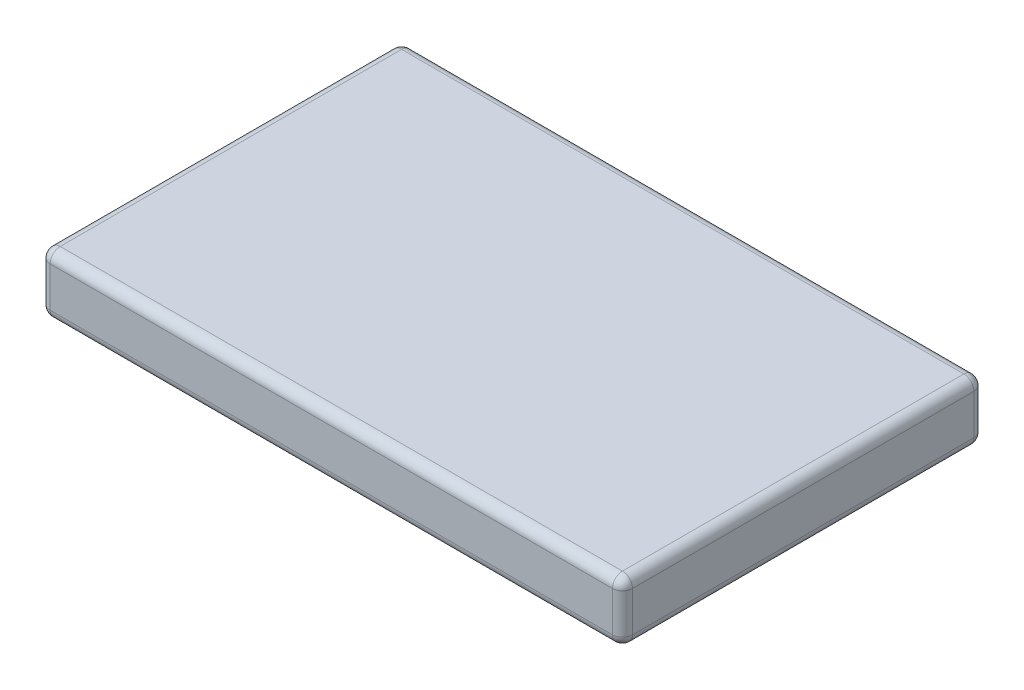
SolidWorks part; units mm, degrees
ref_plane "Plano frontal" through (0, 0, 0) normal (0, 0, 1) x (1, 0, 0)
ref_plane "Plano superior" through (0, 0, 0) normal (0, 1, 0) x (1, 0, 0)
ref_plane "Plano direito" through (0, 0, 0) normal (1, 0, 0) x (0, 0, -1)
sketch "Esboço1" plane through (0, 0, 0) normal (0, 1, 0) x (1, 0, 0)
  line L1 (29, 18) -> (-29, 18)
  line L2 (29, 18) -> (29, -18)
  line L3 (29, -18) -> (-29, -18)
  line L4 (-29, 18) -> (-29, -18)
  line L5 (29, 18) -> (-29, -18) construction
  line L6 (29, -18) -> (-29, 18) construction
  point P0 (0, 0)
  dimension "D1" = 36
  dimension "D2" = 58
extrude "Ressalto-extrusão1" add sketch "Esboço1" along normal blind 6
fillet "Filete1" radius 1 12 edges at (0, 0, 18) (29, 0, 0) (0, 0, -18) (-29, 0, 0) (0, 6, -18) (29, 6, 0) (0, 6, 18) (-29, 6, 0) (-29, 3, -18) (-29, 3, 18) (29, 3, -18) (29, 3, 18)
